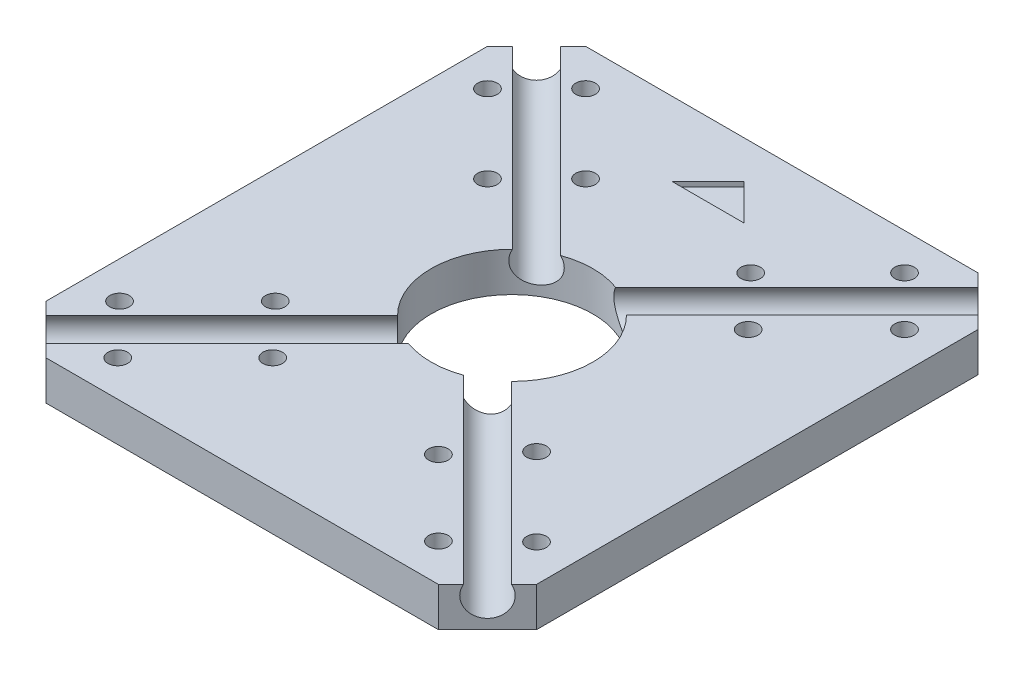
SolidWorks part; units mm, degrees
ref_plane "前视基准面" through (0, 0, 0) normal (0, 0, 1) x (1, 0, 0)
ref_plane "上视基准面" through (0, 0, 0) normal (0, 1, 0) x (1, 0, 0)
ref_plane "右视基准面" through (0, 0, 0) normal (1, 0, 0) x (0, 0, -1)
sketch "草图1" plane through (0, 0, 0) normal (0, 1, 0) x (1, 0, 0)
  line L0 (-40, 55) -> (-50, 45)
  line L5 (-50, 55) -> (50, 55) construction
  line L6 (-50, 55) -> (-50, -55) construction
  line L7 (-50, -55) -> (50, -55) construction
  line L8 (50, 55) -> (50, -55) construction
  line L9 (-40, 55) -> (40, 55)
  line L10 (40, 55) -> (50, 45)
  line L11 (50, 45) -> (50, -45)
  line L12 (50, -45) -> (40, -55)
  line L13 (40, -55) -> (-40, -55)
  line L14 (-40, -55) -> (-50, -45)
  line L15 (-50, -45) -> (-50, 45)
  line L16 (-45, 50) -> (0, 5) construction
  line L17 (45, 50) -> (0, 5) construction
  line L18 (-45, -50) -> (0, -5) construction
  line L19 (0, -5) -> (45, -50) construction
  point P4 (-50, 0)
  point P5 (0, 55)
  point P26 (0, 0)
  dimension "D3" = 10
  dimension "D1" = 100
  dimension "D2" = 110
  dimension "D4" = 10
  dimension "D5" = 10
  dimension "D6" = 10
  dimension "D7" = 10
  dimension "D8" = 10
  dimension "D9" = 10
  dimension "D10" = 10
extrude "凸台-拉伸1" add sketch "草图1" along normal blind 8
sketch "草图3" plane through (0, 8, 0) normal (0, 1, 0) x (1, 0, 0)
  circle A0 centre (0, 0) radius 16.5
extrude "切除-拉伸1" cut sketch "草图3" against normal blind 8
sketch "草图2" plane through (47.5, 0, 47.5) normal (0.7071, 0, 0.7071) x (0.7071, 0, -0.7071)
  line L0 (-10.6066, 0) -> (3.5355, 0) construction
  circle A0 centre (-3.5355, 6) radius 4
  point P2 (-3.5355, 5.6116)
  dimension "D1" = 6
extrude "切除-拉伸2" cut sketch "草图2" against normal blind 60
sketch "草图4" plane through (-47.5, 0, 47.5) normal (-0.7071, 0, 0.7071) x (0.7071, 0, 0.7071)
  line L0 (-3.5355, 0) -> (10.6066, 0) construction
  circle A0 centre (3.5355, 6) radius 4
  dimension "D1" = 6
extrude "切除-拉伸3" cut sketch "草图4" against normal blind 60
sketch "草图5" plane through (-47.5, 0, -47.5) normal (-0.7071, 0, -0.7071) x (-0.7071, 0, 0.7071)
  line L0 (-10.6066, 0) -> (3.5355, 0) construction
  circle A0 centre (-3.5355, 6) radius 4
  dimension "D1" = 6
extrude "切除-拉伸4" cut sketch "草图5" against normal blind 60
sketch "草图6" plane through (47.5, 0, -47.5) normal (0.7071, 0, -0.7071) x (-0.7071, 0, -0.7071)
  line L0 (-3.5355, 0) -> (10.6066, 0) construction
  circle A0 centre (3.5355, 6) radius 4
  dimension "D1" = 6
extrude "切除-拉伸5" cut sketch "草图6" against normal blind 60
sketch "草图7" plane through (0, 8, 0) normal (0, 1, 0) x (1, 0, 0)
  line L0 (0, 47.3345) -> (-7.3855, 39.949)
  line L1 (-7.3855, 39.949) -> (7.3855, 39.949)
  line L2 (7.3855, 39.949) -> (0, 47.3345)
  point P2 (0, 0)
  point P4 (0, 0)
extrude "切除-拉伸6" cut sketch "草图7" against normal blind 1
sketch "草图8" plane through (0, 8, 0) normal (0, 1, 0) x (1, 0, 0)
  line L0 (-40, 55) -> (-3.4948, 18.4948) construction
  line L1 (-3.4948, 18.4948) -> (3.4948, 18.4948) construction
  line L2 (3.4948, 18.4948) -> (40, 55) construction
  line L3 (-50, 45) -> (-15.3687, 10.3687) construction
  line L4 (50, 45) -> (15.3687, 10.3687) construction
  line L5 (-42.5505, 52.4495) -> (-5.6159, 15.5149) construction
  line L6 (-11.6166, 11.7177) -> (-47.4495, 47.5505) construction
  line L7 (5.6159, 15.5149) -> (42.5505, 52.4495) construction
  line L8 (47.4495, 47.5505) -> (11.6166, 11.7177) construction
  line L9 (-30.1016, 49.9082) -> (-45.7119, 34.2979) construction
  line L10 (-14.1913, 33.9979) -> (-29.8016, 18.3876) construction
  line L11 (-50, -45) -> (-15.3687, -10.3687) construction
  line L12 (-40, -55) -> (-4.1185, -19.1185) construction
  line L13 (-4.1185, -19.1185) -> (4.1185, -19.1185) construction
  line L14 (4.1185, -19.1185) -> (40, -55) construction
  line L15 (50, -45) -> (14.7104, -9.7104) construction
  line L16 (11.6166, -11.7177) -> (47.4495, -47.5505) construction
  line L17 (-5.6159, -15.5149) -> (-42.5505, -52.4495) construction
  circle A1 centre (-32.511, 47.511) radius 2
  circle A2 centre (-42.5049, 37.5049) radius 2
  circle A3 centre (-16.5946, 31.5946) radius 2
  circle A4 centre (-26.5946, 21.5946) radius 2
  circle A5 centre (16.8285, 31.8285) radius 2
  circle A6 centre (32.511, 47.511) radius 2
  circle A7 centre (42.5049, 37.5049) radius 2
  circle A8 centre (26.5768, 21.5768) radius 2
  circle A9 centre (-26.6303, -21.6303) radius 2
  circle A10 centre (-16.8946, -31.8946) radius 2
  circle A11 centre (-42.5049, -37.5049) radius 2
  circle A12 centre (-32.6844, -47.6844) radius 2
  circle A13 centre (26.5589, -21.5589) radius 2
  circle A14 centre (17.0625, -32.0625) radius 2
  circle A15 centre (42.5049, -37.5049) radius 2
  circle A16 centre (32.3552, -47.3552) radius 2
  point P72 (-23.4948, 18.4948)
  point P73 (0, 0)
  point P74 (12.3626, 27.3626)
  point P75 (22.5304, 17.5304)
  point P76 (-23.4948, -18.3483)
  point P77 (-13.4948, -28.5721)
  point P78 (22.5304, -17.4465)
  point P79 (17.0625, -32.0625)
  point P80 (26.5589, -21.5589)
  point P81 (-16.8946, -32.0625)
  point P82 (-26.7018, -21.5589)
  point P83 (-26.6303, 21.5946)
  point P84 (17.0625, 31.5946)
  point P85 (26.5589, 21.5946)
extrude "切除-拉伸8" cut sketch "草图8" against normal blind 9
sketch "草图9" plane through (0, 0, 0) normal (0, -1, 0) x (1, 0, 0)
  circle A0 centre (0, 0) radius 30 construction
